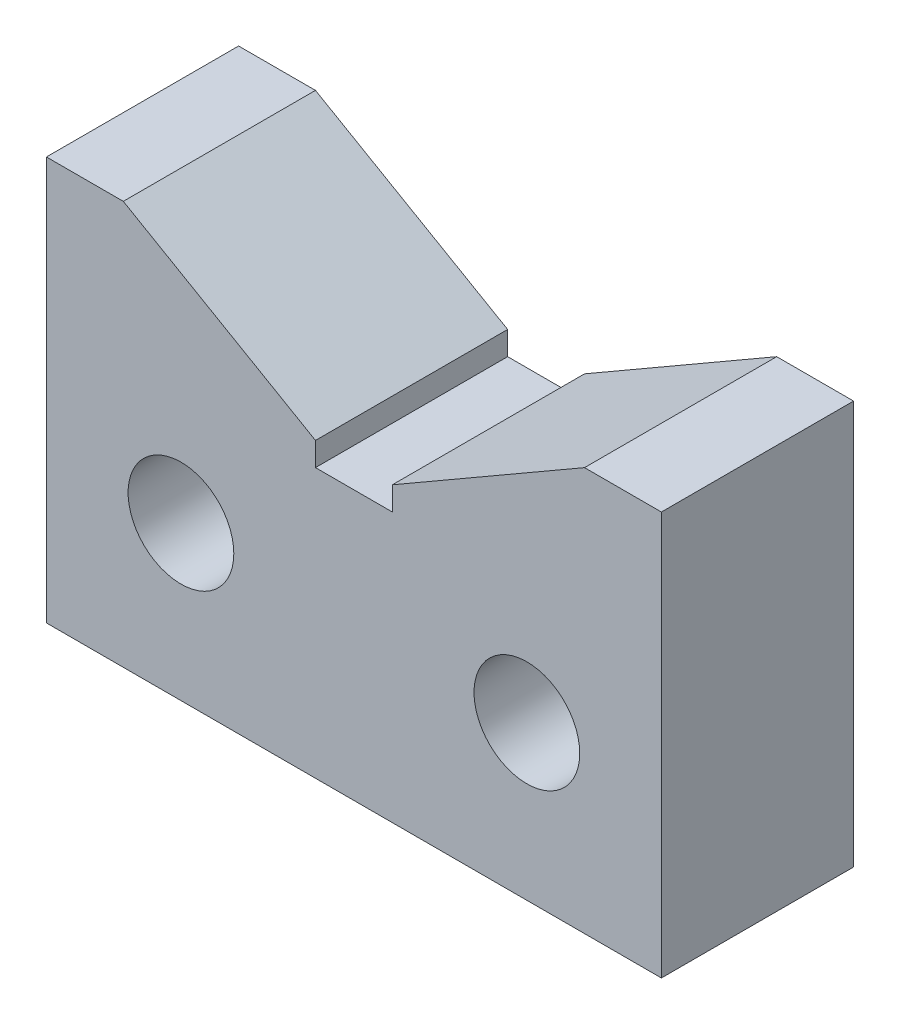
SolidWorks part; units mm, degrees
material "Простая углеродистая сталь"
ref_plane "Спереди" through (0, 0, 0) normal (0, 0, 1) x (1, 0, 0)
ref_plane "Сверху" through (0, 0, 0) normal (0, 1, 0) x (1, 0, 0)
ref_plane "Справа" through (0, 0, 0) normal (1, 0, 0) x (0, 0, -1)
other "Табл. исп."
sketch "Эскиз1" plane through (0, 0, 0) normal (0, 0, 1) x (1, 0, 0)
  line L0 (0, 0) -> (0, 19.4206) construction
  line L1 (16, 0) -> (-16, 0)
  line L2 (-16, 0) -> (-16, 21)
  line L3 (-16, 21) -> (-12, 21)
  line L4 (-12, 21) -> (-2, 15.2265)
  line L5 (-2, 15.2265) -> (-2, 14)
  line L6 (-2, 14) -> (2, 14)
  line L7 (2, 15.2265) -> (2, 14)
  line L8 (12, 21) -> (2, 15.2265)
  line L9 (16, 21) -> (12, 21)
  line L10 (16, 0) -> (16, 21)
  line L11 (2, 15.2265) -> (1.9653, 15.2612)
  circle A0 centre (-9, 8) radius 2.75
  circle A3 centre (9, 8) radius 2.75
  point P10 (0, 14)
  point P16 (0, 0)
  dimension "D8" = 18
  dimension "D9" = 5.5
  dimension "D1" = 4
  dimension "D2" = 24
  dimension "D3" = 32
  dimension "D4" = 7
  dimension "D5" = 120
  dimension "B" = 21
  dimension "b'" = 13
extrude "Бобышка-Вытянуть1" add sketch "Эскиз1" along normal blind 10 contours L1 L0 L6 L5 L4 L3 L2 A0 | L0 L1 L10 L9 L8 L7 L6 A3
